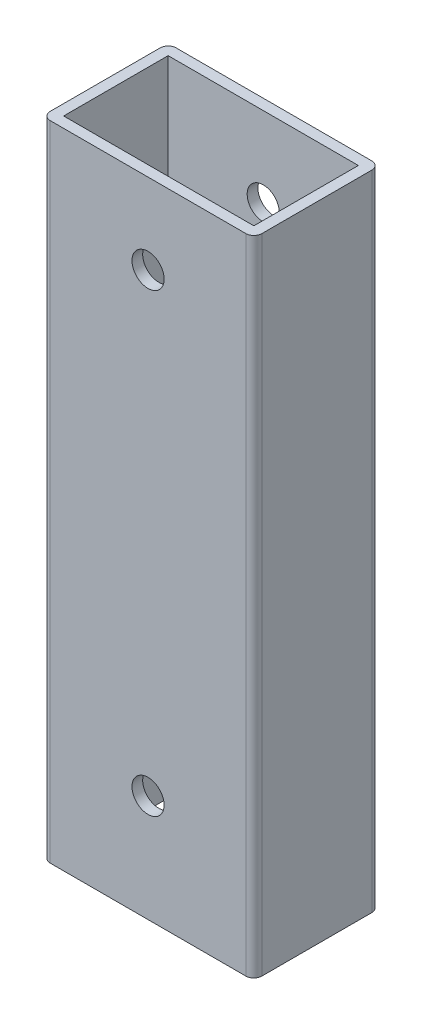
SolidWorks part; units mm, degrees
ref_plane "Front Plane" through (0, 0, 0) normal (0, 0, 1) x (1, 0, 0)
ref_plane "Top Plane" through (0, 0, 0) normal (0, 1, 0) x (1, 0, 0)
ref_plane "Right Plane" through (0, 0, 0) normal (1, 0, 0) x (0, 0, -1)
sketch "Sketch1" plane through (0, 0, 0) normal (0, 1, 0) x (1, 0, 0)
  line L1 (-17.75, -9.75) -> (17.75, -9.75)
  line L2 (-17.75, -9.75) -> (-17.75, 9.75)
  line L3 (-17.75, 9.75) -> (17.75, 9.75)
  line L4 (17.75, -9.75) -> (17.75, 9.75)
  line L5 (-17.75, -9.75) -> (17.75, 9.75) construction
  line L6 (-17.75, 9.75) -> (17.75, -9.75) construction
  line L7 (-19.75, -11.75) -> (19.75, -11.75)
  line L8 (-19.75, -11.75) -> (-19.75, 11.75)
  line L9 (-19.75, 11.75) -> (19.75, 11.75)
  line L10 (19.75, -11.75) -> (19.75, 11.75)
  line L11 (-19.75, -11.75) -> (19.75, 11.75) construction
  line L12 (-19.75, 11.75) -> (19.75, -11.75) construction
  point P0 (0, 0)
  point P6 (0, 0)
  point P11 (18.9738, 11.4949)
  dimension "D1" = 2
  dimension "D2" = 19.5
  dimension "D3" = 2
  dimension "D4" = 35.5
extrude "Boss-Extrude1" add sketch "Sketch1" along normal blind 120
sketch "Sketch2" plane through (0, 0, 9.75) normal (0, 0, -1) x (-1, 0, 0)
  line L0 (0, 0) -> (0, 105) construction
  line L2 (-19.75, 0) -> (19.75, 0) construction
  circle A0 centre (0, 105) radius 3
  circle A1 centre (0, 20) radius 3
  dimension "D1" = 6
  dimension "D2" = 85
  dimension "D3" = 20
extrude "Cut-Extrude1" cut sketch "Sketch2" against normal through all both and the other way through all
fillet "Fillet1" radius 1.5 4 edges at (19.75, 60, 11.75) (-19.75, 60, 11.75) (19.75, 60, -11.75) (-19.75, 60, -11.75)
